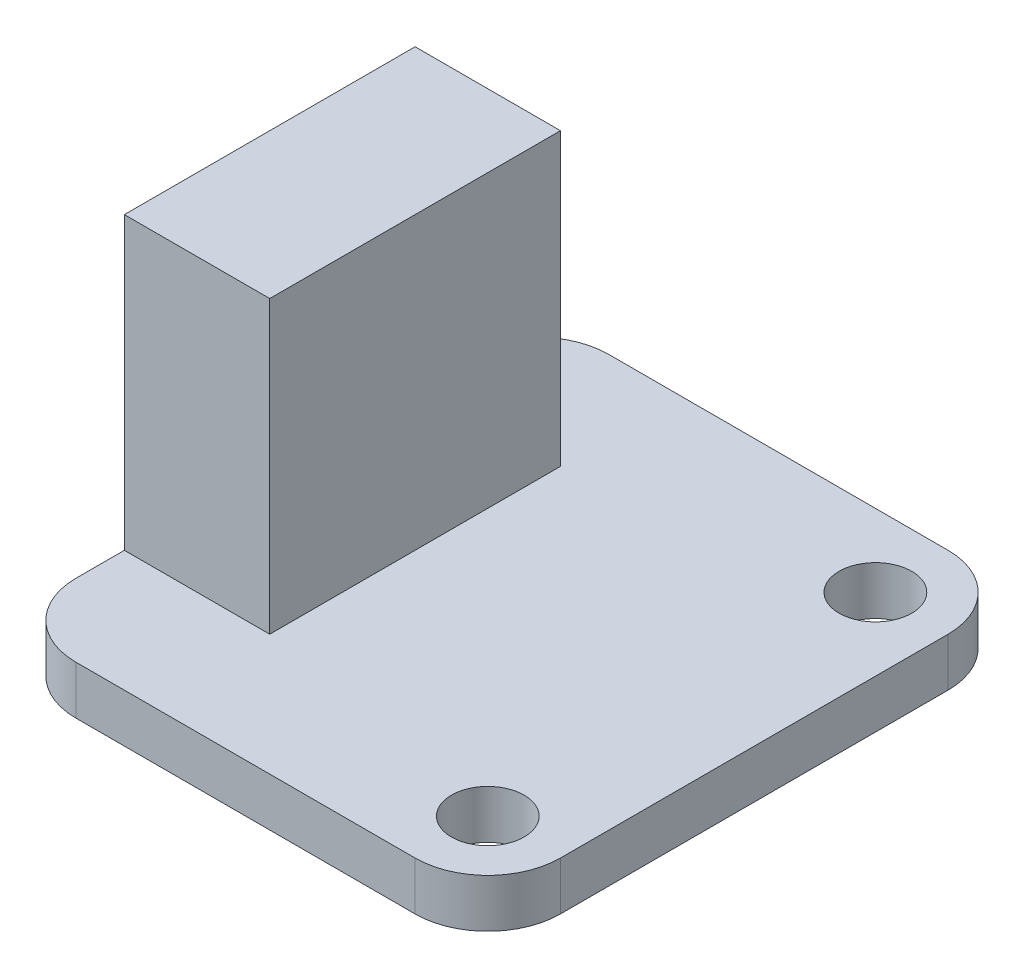
SolidWorks part; units mm, degrees
ref_plane "Front Plane" through (0, 0, 0) normal (0, 0, 1) x (1, 0, 0)
ref_plane "Top Plane" through (0, 0, 0) normal (0, 1, 0) x (1, 0, 0)
ref_plane "Right Plane" through (0, 0, 0) normal (1, 0, 0) x (0, 0, -1)
sketch "Sketch1" plane through (0, 0, 0) normal (0, 1, 0) x (1, 0, 0)
  line L1 (-7, 11) -> (7, 11)
  line L2 (-10, 8) -> (-10, -8)
  line L3 (-7, -11) -> (7, -11)
  line L4 (10, 8) -> (10, -8)
  line L5 (-10, 11) -> (10, -11) construction
  line L6 (-10, -11) -> (10, 11) construction
  circle A0 centre (7, 8) radius 1.5
  circle A1 centre (7, -8) radius 1.5
  arc A2 (10, 8) -> (7, 11) centre (7, 8) ccw
  arc A3 (7, -11) -> (10, -8) centre (7, -8) ccw
  arc A4 (-10, -8) -> (-7, -11) centre (-7, -8) ccw
  arc A5 (-7, 11) -> (-10, 8) centre (-7, 8) ccw
  point P0 (0, 0)
  dimension "D3" = 3
  dimension "D4" = 3
  dimension "D1" = 3
  dimension "D9" = 3
  dimension "22" = 22
  dimension "D2" = 20
  dimension "D5" = 3
  dimension "D6" = 3
  dimension "D7" = 3
  dimension "D8" = 3
extrude "Boss-Extrude1" add sketch "Sketch1" along normal blind 2
sketch "Sketch2" plane through (0, 2, 0) normal (0, 1, 0) x (1, 0, 0)
  line L0 (-10, 8) -> (-10, -8) construction
  line L1 (-10, 6) -> (-4, 6)
  line L2 (-10, 6) -> (-10, -6)
  line L3 (-10, -6) -> (-4, -6)
  line L4 (-4, 6) -> (-4, -6)
  line L5 (-10, 6) -> (-4, -6) construction
  line L6 (-10, -6) -> (-4, 6) construction
  point P0 (-7, 0)
  point P5 (0, 0)
  point P7 (-10, 4.2086)
  dimension "D1" = 6
  dimension "D2" = 12
extrude "Boss-Extrude2" add sketch "Sketch2" along normal blind 12
sketch "Sketch3" plane through (0, 0, 0) normal (0, -1, 0) x (1, 0, 0)
  line L0 (10, 8) -> (10, -8) construction
  line L1 (1, 2) -> (3, 2)
  line L2 (1, 2) -> (1, -2)
  line L3 (1, -2) -> (3, -2)
  line L4 (3, 2) -> (3, -2)
  line L5 (1, 2) -> (3, -2) construction
  line L6 (1, -2) -> (3, 2) construction
  point P0 (2, 0)
  point P5 (0, 0)
  dimension "D1" = 4
  dimension "D2" = 2
  dimension "D3" = 7
extrude "Boss-Extrude3" add sketch "Sketch3" along normal blind 2
